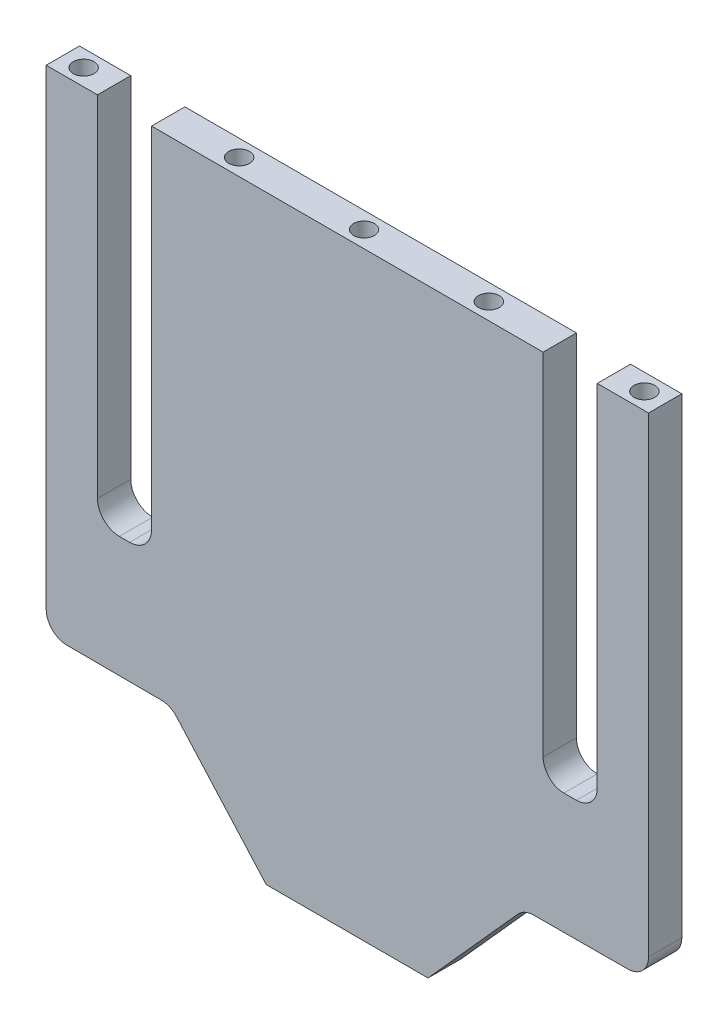
SolidWorks part; units mm, degrees
ref_plane "Front Plane" through (0, 0, 0) normal (0, 0, 1) x (1, 0, 0)
ref_plane "Top Plane" through (0, 0, 0) normal (0, 1, 0) x (1, 0, 0)
ref_plane "Right Plane" through (0, 0, 0) normal (1, 0, 0) x (0, 0, -1)
sketch "Sketch1" plane through (0, 0, 0) normal (0, 0, 1) x (1, 0, 0)
  line L4 (70, 309.9858) -> (85.2992, 309.9858)
  line L6 (43.2101, 271.7903) -> (49.7246, 305.9232)
  line L7 (42.2614, 270.1156) -> (0.0495, 220.7861)
  line L8 (0.0495, 220.7861) -> (42.9, 220.7861) construction
  line L9 (42.9, 220.7861) -> (42.9, 270.8599) construction
  line L10 (96.9829, 220.8599) -> (96.9829, 270.8599) construction
  line L11 (112.4871, 25.7747) -> (89.3829, 25.7747) construction
  line L12 (27.5129, 25.7747) -> (50.5, 25.7747) construction
  line L13 (25.2828, 25.7823) -> (2.6386, 25.8599)
  line L14 (96.6727, 271.7903) -> (90.212, 305.9159)
  line L15 (70, 329.5221) -> (70, -78.2612) construction
  line L18 (50.5, 25.7747) -> (50.5, 0) construction
  line L19 (70, 309.9858) -> (54.636, 309.9858)
  line L20 (135.9829, 220.8599) -> (96.9829, 220.8599) construction
  line L21 (139.9505, 220.7861) -> (135.9829, 220.8599) construction
  line L25 (89.3829, 25.7747) -> (89.3829, 0) construction
  line L27 (89.3829, 0) -> (50.5, 0)
  line L28 (15.2188, 54.8072) -> (17.7021, 54.8072)
  line L35 (125.0395, 54.8072) -> (122.0396, 54.8072)
  line L36 (122.0396, 194.8072) -> (125.0395, 194.8072)
  line L37 (117.0396, 59.8072) -> (117.0396, 189.8072)
  line L38 (130.0395, 189.8072) -> (130.0395, 59.8072)
  line L39 (142.3614, 214.274) -> (142.3614, 30.8599)
  line L40 (97.6215, 270.1156) -> (139.9505, 220.7861)
  line L41 (-2.3614, 214.274) -> (-2.3614, 30.8599)
  line L42 (9.9605, 189.8072) -> (9.9605, 60.0656)
  line L43 (22.9604, 60.0656) -> (22.9604, 189.8072)
  line L44 (17.9604, 194.8072) -> (14.9605, 194.8072)
  line L45 (28.9972, 24.1103) -> (50.5, 0)
  line L46 (114.7172, 25.7823) -> (137.3614, 25.8599)
  line L47 (89.3829, 0) -> (111.0028, 24.1103)
  arc A1 (42.2614, 270.1156) -> (43.2101, 271.7903) centre (38.4667, 273.3715) ccw
  arc A5 (97.6215, 270.1156) -> (96.6727, 271.7903) centre (101.4161, 273.3715) cw
  arc A8 (137.3614, 25.8599) -> (142.3614, 30.8599) centre (137.3614, 30.8599) ccw
  arc A9 (2.6386, 25.8599) -> (-2.3614, 30.8599) centre (2.6386, 30.8599) cw
  arc A10 (49.7246, 305.9232) -> (54.636, 309.9858) centre (54.636, 304.9858) cw
  arc A11 (85.2992, 309.9858) -> (90.212, 305.9159) centre (85.2992, 304.9858) cw
  arc A12 (139.9505, 220.7861) -> (142.3614, 214.274) centre (132.3614, 214.274) cw
  arc A13 (0.0495, 220.7861) -> (-2.3614, 214.274) centre (7.6386, 214.274) ccw
  arc A14 (25.2828, 25.7823) -> (28.9972, 24.1103) centre (25.2657, 20.7823) cw
  arc A15 (114.7172, 25.7823) -> (111.0028, 24.1103) centre (114.7343, 20.7823) ccw
  arc A16 (17.9604, 194.8072) -> (22.9604, 189.8072) centre (17.9604, 189.8072) cw
  arc A17 (9.9605, 189.8072) -> (14.9605, 194.8072) centre (14.9605, 189.8072) cw
  arc A18 (125.0395, 54.8072) -> (130.0395, 59.8072) centre (125.0395, 59.8072) ccw
  arc A19 (122.0396, 54.8072) -> (117.0396, 59.8072) centre (122.0396, 59.8072) cw
  arc A20 (125.0395, 194.8072) -> (130.0395, 189.8072) centre (125.0395, 189.8072) cw
  arc A21 (117.0396, 189.8072) -> (122.0396, 194.8072) centre (122.0396, 189.8072) cw
  arc A22 (17.7021, 54.8072) -> (22.9604, 60.0656) centre (17.7021, 60.0656) ccw
  arc A23 (15.2188, 54.8072) -> (9.9605, 60.0656) centre (15.2188, 60.0656) cw
  point P18 (22.9604, 194.8072)
  point P51 (9.9605, 194.8072)
  point P57 (130.0395, 54.8072)
  point P61 (117.0396, 54.8072)
  point P67 (130.0395, 194.8072)
  point P70 (117.0396, 194.8072)
  point P77 (22.9604, 54.8072)
  point P80 (9.9605, 54.8072)
  dimension "D1" = 5
  dimension "D2" = 5
  dimension "D3" = 5
  dimension "D4" = 10
  dimension "D5" = 5
  dimension "D6" = 5
  dimension "D7" = 5.2583
extrude "Boss-Extrude1" add sketch "Sketch1" along normal blind 8
sketch "Sketch3" plane through (0, 0, 0) normal (0, 0, -1) x (-1, 0, 0)
  line L1 (-142.3614, 144.0523) -> (2.3614, 144.0523)
  line L3 (-142.3614, 30.8599) -> (-142.3614, 214.274) construction
  line L6 (2.3614, 214.274) -> (2.3614, 30.8599) construction
split "Split1" trim tools "Sketch3" bodies to split 101 resulting bodies 104 108
ref_plane "Plane4" through (0, 144.0523, 0) normal (0, 1, 0) x (1, 0, 0)
sketch "Sketch4" plane through (0, 144.0523, 0) normal (0, -1, 0) x (-1, 0, 0)
  line L0 (-3.7995, -8) -> (-3.7995, -4)
  line L2 (2.3614, -8) -> (-9.9605, -8) construction
  circle A1 centre (-70, -4) radius 2.5
  circle A2 centre (-40, -4) radius 2.5
  circle A3 centre (-100, -4) radius 2.5
  circle A5 centre (-137.3614, -4) radius 2.5
  circle A6 centre (-3.7995, -4) radius 2.5
sketch "Sketch5" plane through (0, 144.0523, -115.3599) normal (0, -1, 0) x (1, 0, 0)
  circle A1 centre (70, 119.3599) radius 2.5
  circle A2 centre (100, 119.3599) radius 2.5
  circle A3 centre (40, 119.3599) radius 2.5
  circle A5 centre (2.6386, 119.3599) radius 2.5
  circle A6 centre (137.3614, 119.3599) radius 2.5
extrude "Cut-Extrude6" cut sketch "Sketch5" along direction (0, -1, 0) on the side of the normal blind 10 contours A5 | A3 | A1 | A2 | A6
extrude "Cut-Extrude7" cut sketch "Sketch4" against normal blind 10
sketch "Sketch6" plane through (0, 0, 8) normal (0, 0, 1) x (1, 0, 0)
  circle A0 centre (50.0001, 267.9803) radius 1.5
  circle A1 centre (90.0001, 267.9803) radius 1.5
  circle A2 centre (90.0001, 227.9803) radius 1.5
  circle A3 centre (50.0001, 227.9803) radius 1.5
extrude "Cut-Extrude8" cut sketch "Sketch6" against normal through all
sketch "Sketch7" plane through (0, 0, 0) normal (0, 0, -1) x (-1, 0, 0)
  line L10 (-94.5001, 223.4803) -> (-94.5001, 272.4803)
  line L11 (-47.0001, 270.9803) -> (-47.0001, 252.9803)
  line L12 (-45.5001, 272.4803) -> (-45.5001, 223.4803)
  line L13 (-45.5001, 223.4803) -> (-94.5001, 223.4803)
  line L14 (-93.0001, 270.9803) -> (-75.0001, 270.9803)
  line L15 (-93.0001, 224.9803) -> (-75.0001, 224.9803)
  line L16 (-93.0001, 224.9803) -> (-93.0001, 242.9803)
  line L18 (-65.0001, 270.9803) -> (-65.0001, 252.9803)
  line L19 (-65.0001, 224.9803) -> (-47.0001, 224.9803)
  line L20 (-45.5001, 272.4803) -> (-94.5001, 272.4803)
  line L21 (-75.0001, 270.9803) -> (-75.0001, 252.9803)
  line L22 (-47.0001, 252.9803) -> (-65.0001, 252.9803)
  line L23 (-47.0001, 242.9803) -> (-47.0001, 224.9803)
  line L24 (-93.0001, 242.9803) -> (-75.0001, 242.9803)
  line L25 (-65.0001, 270.9803) -> (-47.0001, 270.9803)
  line L26 (-75.0001, 252.9803) -> (-93.0001, 252.9803)
  line L27 (-65.0001, 242.9803) -> (-47.0001, 242.9803)
  line L28 (-65.0001, 242.9803) -> (-65.0001, 224.9803)
  line L29 (-75.0001, 242.9803) -> (-75.0001, 224.9803)
  line L30 (-93.0001, 252.9803) -> (-93.0001, 270.9803)
extrude "Boss-Extrude2" add sketch "Sketch7" along normal blind 15
sketch "Sketch8" plane through (0, 0, -15) normal (0, 0, -1) x (-1, 0, 0)
  line L0 (-45.5001, 272.4803) -> (-94.5001, 272.4803)
  line L1 (-94.5001, 272.4803) -> (-94.5001, 223.4803)
  line L2 (-94.5001, 223.4803) -> (-45.5001, 223.4803)
  line L3 (-94.5001, 223.4803) -> (-45.5001, 223.4803) construction
  line L4 (-94.5001, 223.4803) -> (-45.5001, 223.4803) construction
  line L5 (-45.5001, 223.4803) -> (-45.5001, 272.4803)
  circle A0 centre (-50.0001, 267.9803) radius 1.5
  circle A1 centre (-90.0001, 267.9803) radius 1.5
  circle A2 centre (-50.0001, 227.9803) radius 1.5
  circle A3 centre (-90.0001, 227.9803) radius 1.5
extrude "Boss-Extrude3" add sketch "Sketch8" along normal blind 10
sketch "Sketch9" plane through (0, 0, 8) normal (0, 0, 1) x (1, 0, 0)
  line L9 (45.5001, 272.4803) -> (94.5001, 272.4803)
  line L10 (45.5001, 272.4803) -> (45.5001, 223.4803)
  line L11 (45.5001, 223.4803) -> (94.5001, 223.4803)
  line L12 (94.5001, 272.4803) -> (94.5001, 223.4803)
extrude "Cut-Extrude9" cut sketch "Sketch9" against normal blind 8
sketch "Sketch10" plane through (0, 0, 0) normal (0, 0, 1) x (1, 0, 0)
  line L17 (94.5001, 223.4803) -> (45.5001, 223.4803)
  line L18 (45.5001, 223.4803) -> (45.5001, 224.9803)
  line L19 (45.5001, 272.4803) -> (45.5001, 223.4803) construction
  line L23 (47.0001, 242.9803) -> (65.0001, 242.9803)
  line L24 (47.0001, 242.9803) -> (47.0001, 224.9803)
  line L26 (47.0001, 224.9803) -> (65.0001, 224.9803)
  line L27 (65.0001, 242.9803) -> (65.0001, 224.9803)
  line L29 (45.5001, 223.4803) -> (45.5001, 272.4803) construction
  line L30 (45.5001, 242.9803) -> (45.5001, 224.9803)
  line L31 (45.5001, 272.4803) -> (94.5001, 272.4803)
  line L32 (94.5001, 272.4803) -> (94.5001, 223.4803)
  line L40 (75.0001, 242.9803) -> (93.0001, 242.9803)
  line L41 (75.0001, 242.9803) -> (75.0001, 224.9803)
  line L42 (75.0001, 224.9803) -> (93.0001, 224.9803)
  line L43 (93.0001, 242.9803) -> (93.0001, 224.9803)
  line L44 (75.0001, 270.9803) -> (93.0001, 270.9803)
  line L45 (75.0001, 270.9803) -> (75.0001, 252.9803)
  line L46 (75.0001, 252.9803) -> (93.0001, 252.9803)
  line L47 (93.0001, 270.9803) -> (93.0001, 252.9803)
  line L48 (47.0001, 270.9803) -> (65.0001, 270.9803)
  line L49 (47.0001, 270.9803) -> (47.0001, 252.9803)
  line L50 (47.0001, 252.9803) -> (65.0001, 252.9803)
  line L51 (65.0001, 270.9803) -> (65.0001, 252.9803)
  line M21 (93.0001, 224.9803) -> (75.0001, 224.9803)
  line M22 (75.0001, 224.9803) -> (75.0001, 242.9803)
  line M23 (75.0001, 242.9803) -> (93.0001, 242.9803)
  line M24 (93.0001, 242.9803) -> (93.0001, 224.9803)
  line M25 (65.0001, 224.9803) -> (47.0001, 224.9803)
  line M26 (47.0001, 224.9803) -> (47.0001, 242.9803)
  line M27 (47.0001, 242.9803) -> (65.0001, 242.9803)
  line M28 (65.0001, 242.9803) -> (65.0001, 224.9803)
  line M29 (65.0001, 270.9803) -> (65.0001, 252.9803)
  line M30 (65.0001, 252.9803) -> (47.0001, 252.9803)
  line M31 (47.0001, 252.9803) -> (47.0001, 270.9803)
  line M32 (47.0001, 270.9803) -> (65.0001, 270.9803)
  line M33 (93.0001, 252.9803) -> (75.0001, 252.9803)
  line M34 (75.0001, 252.9803) -> (75.0001, 270.9803)
  line M35 (75.0001, 270.9803) -> (93.0001, 270.9803)
  line M36 (93.0001, 270.9803) -> (93.0001, 252.9803)
  line M37 (45.5001, 272.4803) -> (45.5001, 223.4803)
  line M38 (45.5001, 223.4803) -> (94.5001, 223.4803)
  line M39 (94.5001, 223.4803) -> (94.5001, 272.4803)
  line M40 (94.5001, 272.4803) -> (45.5001, 272.4803)
extrude "Boss-Extrude4" add sketch "Sketch10" along normal blind 8 contours M40 M37 M38 M39 M36 M33 M34 M35 M32 M29 M30 M31 M28 M25 M26 M27 M24 M21 M22 M23
sketch "Sketch12" plane through (0, 0, 0) normal (0, 0, -1) x (-1, 0, 0)
  circle A0 centre (-102.9604, 197.5034) radius 2.5
  circle A1 centre (-35.9604, 197.5034) radius 2.5
  circle A2 centre (-35.9604, 157.5034) radius 2.5
  circle A3 centre (-102.9604, 157.5034) radius 2.5
extrude "Cut-Extrude10" cut sketch "Sketch12" against normal through all
delete or keep bodies "Body-Delete/Keep 1" type delete bodies bodies 118
sketch "Sketch13" plane through (0, 0, 0) normal (0, 0, -1) x (-1, 0, 0)
  line L1 (-29.9604, 140.2101) -> (-109.9604, 140.2101)
  line L2 (-29.9604, 140.2101) -> (-29.9604, 40.2101)
  line L3 (-29.9604, 40.2101) -> (-109.9604, 40.2101)
  line L4 (-109.9604, 140.2101) -> (-109.9604, 40.2101)
